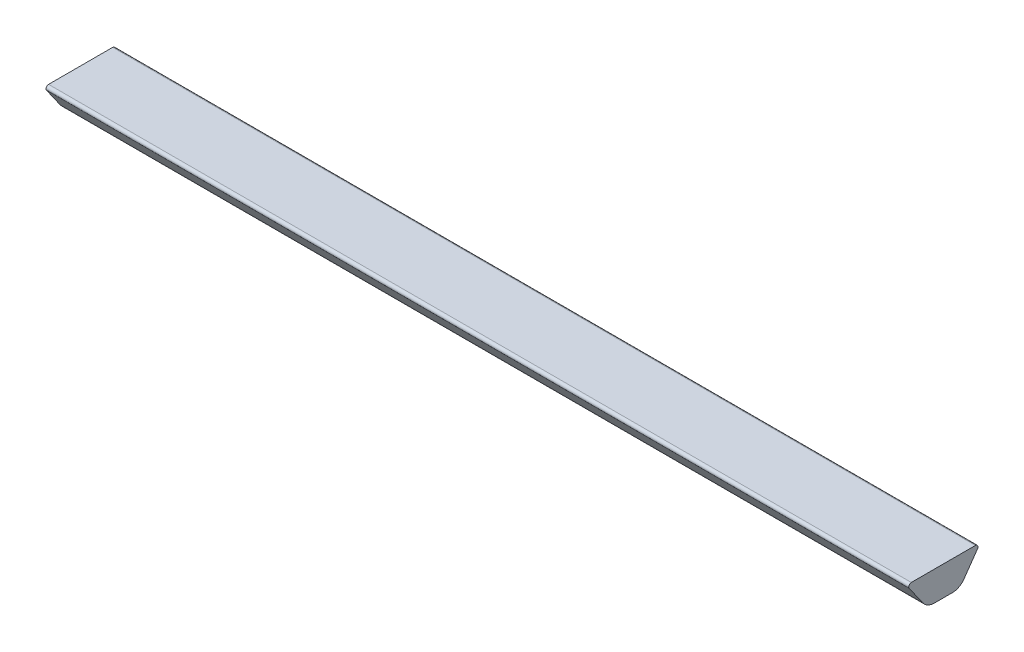
SolidWorks part; units mm, degrees
material "6061-T6 (SS)"
ref_plane "Front Plane" through (0, 0, 0) normal (0, 0, 1) x (1, 0, 0)
ref_plane "Top Plane" through (0, 0, 0) normal (0, 1, 0) x (1, 0, 0)
ref_plane "Right Plane" through (0, 0, 0) normal (1, 0, 0) x (0, 0, -1)
sketch "Sketch1" plane through (0, 0, 0) normal (1, 0, 0) x (0, 0, -1)
  line L0 (0, 0) -> (14.8, 0) construction
  line L1 (14.8, 0) -> (10.65, -5.905) construction
  line L2 (10.65, -5.905) -> (4.15, -5.905) construction
  line L3 (4.15, -5.905) -> (0, 0) construction
  line L4 (7.4, -5.905) -> (7.4, 0) construction
  line L5 (0.0978, -0.0508) -> (14.7022, -0.0508)
  line L6 (14.7022, -0.0508) -> (10.6236, -5.8542)
  line L7 (10.6236, -5.8542) -> (4.1764, -5.8542)
  line L8 (4.1764, -5.8542) -> (0.0978, -0.0508)
  dimension "D1" = 14.8
  dimension "D2" = 6.5
  dimension "D3" = 5.905
  dimension "D4" = 0.0508
extrude "Boss-Extrude1" add sketch "Sketch1" along normal blind 170.1657
fillet "Fillet1" radius 0.508 2 edges at (85.0829, -0.0508, -14.7022) (85.0829, -0.0508, -0.0978)
ref_plane "Plane1" through (0, 0, -7.33) normal (0, 0, 1) x (1, 0, 0)
fillet "Fillet2" radius 2.794 2 edges at (85.0829, -5.8542, -10.6236) (85.0829, -5.8542, -4.1764)
